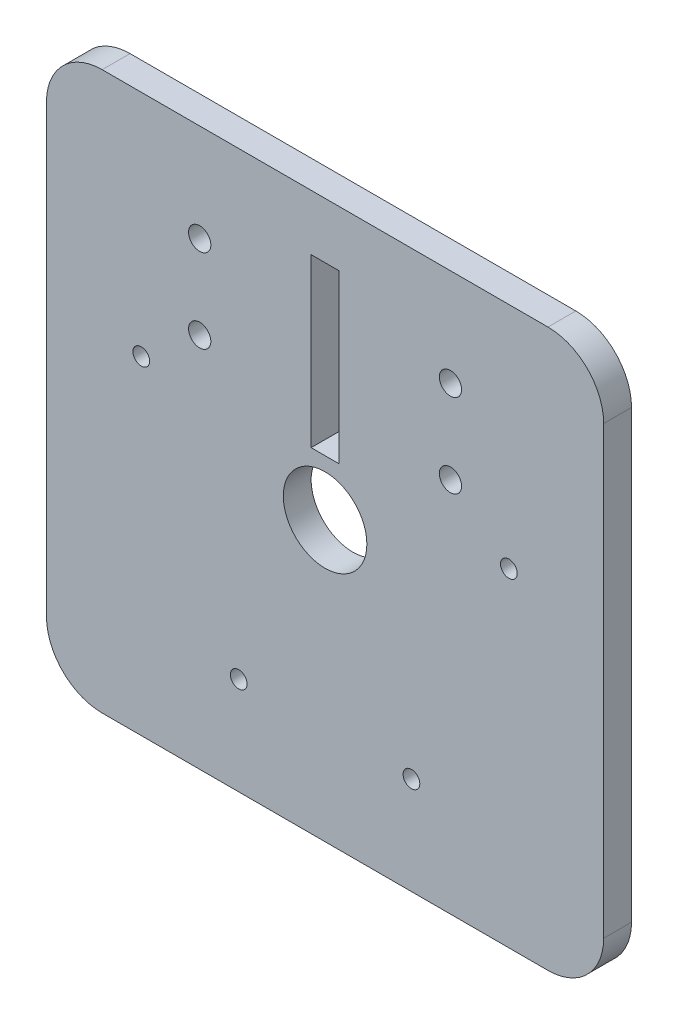
SolidWorks part; units mm, degrees
ref_plane "Alzado" through (0, 0, 0) normal (0, 0, 1) x (1, 0, 0)
ref_plane "Planta" through (0, 0, 0) normal (0, 1, 0) x (1, 0, 0)
ref_plane "Vista lateral" through (0, 0, 0) normal (1, 0, 0) x (0, 0, -1)
sketch "Croquis1" plane through (0, 0, 0) normal (0, 0, 1) x (1, 0, 0)
  line L2 (-123.7732, 29.8118) -> (-123.7732, -70.1882)
  line L3 (-123.7732, -70.1882) -> (-23.7732, -70.1882)
  line L4 (-23.7732, 29.8118) -> (-23.7732, -70.1882)
  line L9 (-123.7732, 29.8118) -> (-23.7732, 29.8118)
  line L11 (-76.2732, 19.8118) -> (-71.2732, 19.8118)
  line L12 (-76.2732, 19.8118) -> (-76.2732, -10.1882)
  line L13 (-76.2732, -10.1882) -> (-71.2732, -10.1882)
  line L14 (-71.2732, 19.8118) -> (-71.2732, -10.1882)
  circle A0 centre (-73.7732, -20.1882) radius 7.5
  point P8 (-73.7732, 19.8118)
  point P9 (-73.7732, 29.8118)
  point P12 (0, 0)
  point P13 (-73.7732, -10.1882)
  dimension "D6" = 10
  dimension "D7" = 15
  dimension "D1" = 100
  dimension "D2" = 100
  dimension "D3" = 10
  dimension "D4" = 30
  dimension "D5" = 5
extrude "Saliente-Extruir1" add sketch "Croquis1" along normal blind 5
fillet "Redondeo1" radius 10 4 edges at (-23.7732, -70.1882, 2.5) (-123.7732, -70.1882, 2.5) (-23.7732, 29.8118, 2.5) (-123.7732, 29.8118, 2.5)
sketch "Croquis3" plane through (0, 0, 0) normal (0, 0, -1) x (-1, 0, 0)
  circle A0 centre (106.7578, -11.2516) radius 1.5 construction
  circle A1 centre (40.7886, -11.2516) radius 1.5 construction
  circle A2 centre (89.2732, -52.6882) radius 1.5 construction
  circle A3 centre (58.2732, -52.6882) radius 1.5 construction
  circle A4 centre (106.7578, -11.2516) radius 1.5
  circle A5 centre (40.7886, -11.2516) radius 1.5
  circle A6 centre (89.2732, -52.6882) radius 1.5
  circle A7 centre (58.2732, -52.6882) radius 1.5
extrude "Cortar-Extruir1" cut sketch "Croquis3" against normal up to surface (5 mm away) up to face at (-73.7732, -20.1882, 5)
sketch "Croquis4" plane through (0, 0, 5) normal (0, 0, 1) x (1, 0, 0)
  line L0 (-71.2732, 19.8118) -> (-76.2732, 19.8118) construction
  line L1 (-71.2732, -10.1882) -> (-71.2732, 19.8118) construction
  line L2 (-73.7732, 19.8118) -> (-73.7732, -10.1882) construction
  line L3 (-76.2732, -10.1882) -> (-71.2732, -10.1882) construction
  line L4 (-76.2732, 4.8118) -> (-71.2732, 4.8118) construction
  line L5 (-76.2732, 19.8118) -> (-76.2732, -10.1882) construction
  circle A0 centre (-51.2732, 12.3118) radius 2
  circle A1 centre (-96.2732, 12.3118) radius 2
  circle A2 centre (-96.2732, -2.6882) radius 2
  circle A3 centre (-51.2732, -2.6882) radius 2
  dimension "D1" = 4
  dimension "D2" = 7.5
  dimension "D3" = 20
extrude "Cortar-Extruir2" cut sketch "Croquis4" against normal up to next
